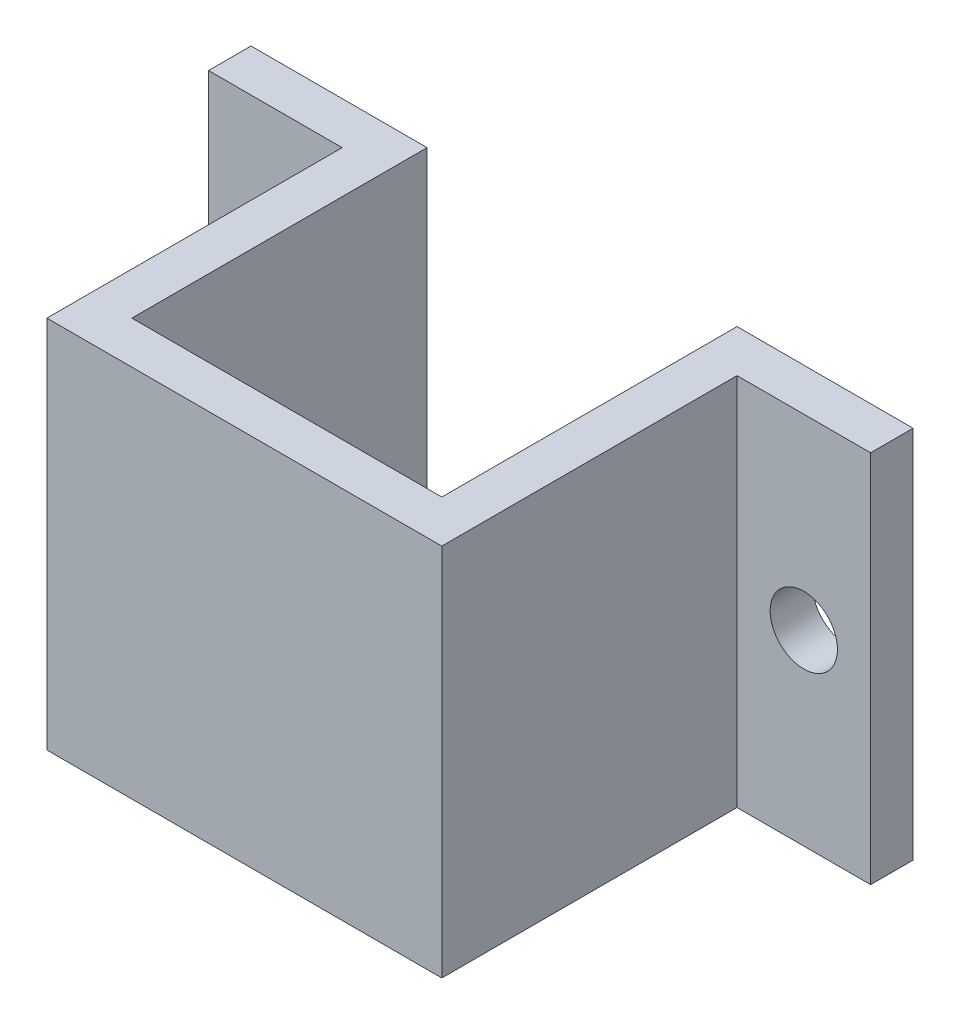
SolidWorks part; units mm, degrees
material "6061 Alloy"
ref_plane "Front Plane" through (0, 0, 0) normal (0, 0, 1) x (1, 0, 0)
ref_plane "Top Plane" through (0, 0, 0) normal (0, 1, 0) x (1, 0, 0)
ref_plane "Right Plane" through (0, 0, 0) normal (1, 0, 0) x (0, 0, -1)
sketch "Sketch1" plane through (0, 0, 0) normal (0, 1, 0) x (1, 0, 0)
  line L0 (-7.39, 0) -> (7.39, 0)
  line L1 (7.39, 0) -> (7.39, 11.05)
  line L2 (7.39, 11.05) -> (12.39, 11.05)
  line L3 (12.39, 11.05) -> (12.39, 12.64)
  line L4 (12.39, 12.64) -> (5.8, 12.64)
  line L5 (5.8, 12.64) -> (5.8, 1.59)
  line L6 (5.8, 1.59) -> (-5.8, 1.59)
  line L7 (-5.8, 1.59) -> (-5.8, 12.64)
  line L8 (-5.8, 12.64) -> (-12.39, 12.64)
  line L9 (-12.39, 12.64) -> (-12.39, 11.05)
  line L10 (-12.39, 11.05) -> (-7.39, 11.05)
  line L11 (-7.39, 11.05) -> (-7.39, 0)
  point P13 (-9.89, 11.05)
  point P15 (0, 0)
  dimension "D1" = 1.59
  dimension "D2" = 1.59
  dimension "D3" = 1.59
  dimension "D4" = 1.59
  dimension "D5" = 1.59
  dimension "D6" = 11.05
  dimension "D7" = 11.6
  dimension "D8" = 6.59
  dimension "D9" = 6.59
extrude "Boss-Extrude1" add sketch "Sketch1" along normal blind 14
sketch "Sketch2" plane through (0, 0, -11.05) normal (0, 0, 1) x (1, 0, 0)
  line L0 (-12.39, 14) -> (-12.39, 0) construction
  line L1 (12.39, 14) -> (12.39, 0) construction
  line L4 (-12.39, 14) -> (-7.39, 14) construction
  circle A0 centre (-9.89, 7) radius 1.2591
  circle A1 centre (9.89, 7) radius 1.2591
  dimension "D4" = 2.5182
  dimension "D1" = 2.5
  dimension "D2" = 2.5
  dimension "D3" = 7
extrude "Cut-Extrude1" cut sketch "Sketch2" against normal blind 14
